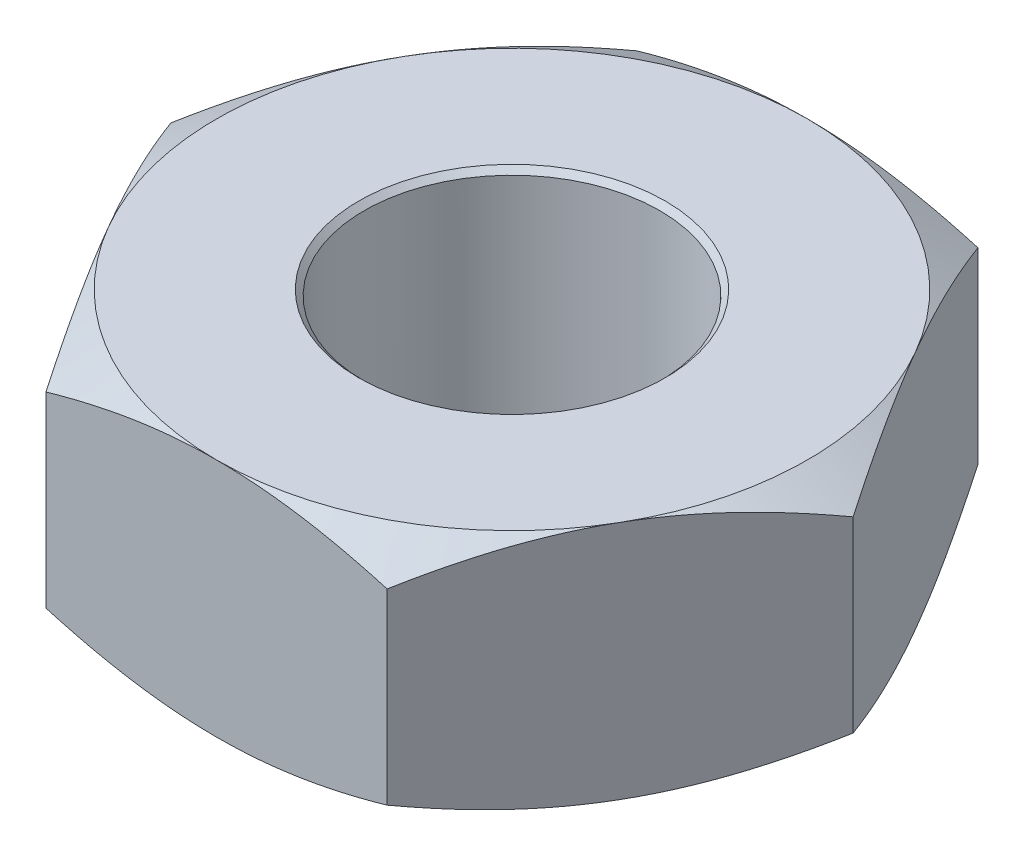
SolidWorks part; units mm, degrees
ref_plane "Front Plane" through (0, 0, 0) normal (0, 0, 1) x (1, 0, 0)
ref_plane "Top Plane" through (0, 0, 0) normal (0, 1, 0) x (1, 0, 0)
ref_plane "Right Plane" through (0, 0, 0) normal (1, 0, 0) x (0, 0, -1)
sketch "Sketch2" plane through (0, 0, 0) normal (0, 1, 0) x (1, 0, 0)
  line L1 (4.6188, 0) -> (2.3094, 4)
  line L2 (2.3094, 4) -> (-2.3094, 4)
  line L3 (-2.3094, 4) -> (-4.6188, 0)
  line L4 (-4.6188, 0) -> (-2.3094, -4)
  line L5 (-2.3094, -4) -> (2.3094, -4)
  line L6 (2.3094, -4) -> (4.6188, 0)
  circle A0 centre (0, 0) radius 2
  circle A1 centre (0, 0) radius 4 construction
  dimension "D1" = 4
  dimension "D2" = 8
extrude "Boss-Extrude1" add sketch "Sketch2" along normal blind 3.25
sketch "Sketch3" plane through (0, 0, 0) normal (0, 1, 0) x (1, 0, 0)
  circle A0 centre (0, 0) radius 4 construction
  circle A1 centre (0, 0) radius 4
extrude "Cut-Extrude1" cut sketch "Sketch3" along normal blind 3.25 draft 60 flip side to cut
sketch "Sketch4" plane through (0, 3.25, 0) normal (0, 1, 0) x (1, 0, 0)
  circle A1 centre (0, 0) radius 4
  circle A2 centre (0, 0) radius 4
  dimension "D1" = 0
extrude "Cut-Extrude2" cut sketch "Sketch4" against normal blind 3.25 draft 60 flip side to cut
chamfer "Chamfer1" distance 0.075 angle 45 2 edges at (0, 0, 2) (0, 3.25, 2)
